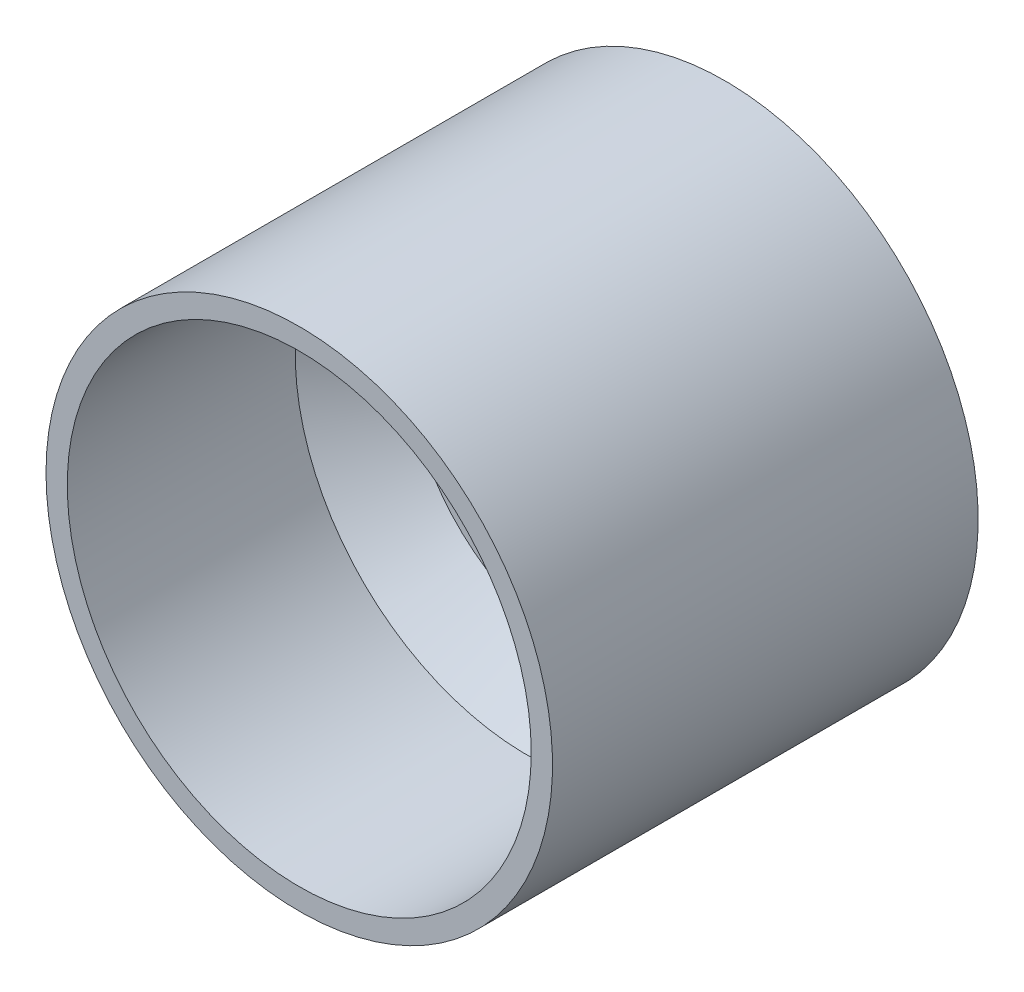
SolidWorks part; units mm, degrees
ref_plane "Front Plane" through (0, 0, 0) normal (1, 0, 0) x (0, 1, 0)
ref_plane "Top Plane" through (0, 0, 0) normal (0, 0, 1) x (0, 1, 0)
ref_plane "Right Plane" through (0, 0, 0) normal (0, 1, 0) x (-1, 0, 0)
sketch "Sketch1" plane through (0, 0, 0) normal (0, 0, 1) x (0, 1, 0)
  circle A0 centre (0, 0) radius 45.339
  dimension "D1" = 90.678
extrude "Boss-Extrude2" add sketch "Sketch1" along normal mid plane 76.2 contours A0
sketch "Sketch3" plane through (0, 0, 38.1) normal (0, 0, 1) x (1, 0, 0)
  circle A0 centre (0, 0) radius 41.529
  dimension "D1" = 83.058
extrude "Cut-Extrude1" cut sketch "Sketch3" against normal blind 50.8
sketch "Sketch4" plane through (0, 0, -38.1) normal (0, 0, -1) x (1, 0, 0)
  circle A0 centre (0, 0) radius 20.0025
  dimension "D1" = 40.005
extrude "Cut-Extrude2" cut sketch "Sketch4" against normal blind 25.4
chamfer "Chamfer1" distance 10 angle 45 2 edges at (41.529, 0, -12.7) (-20.0025, 0, -12.7)
